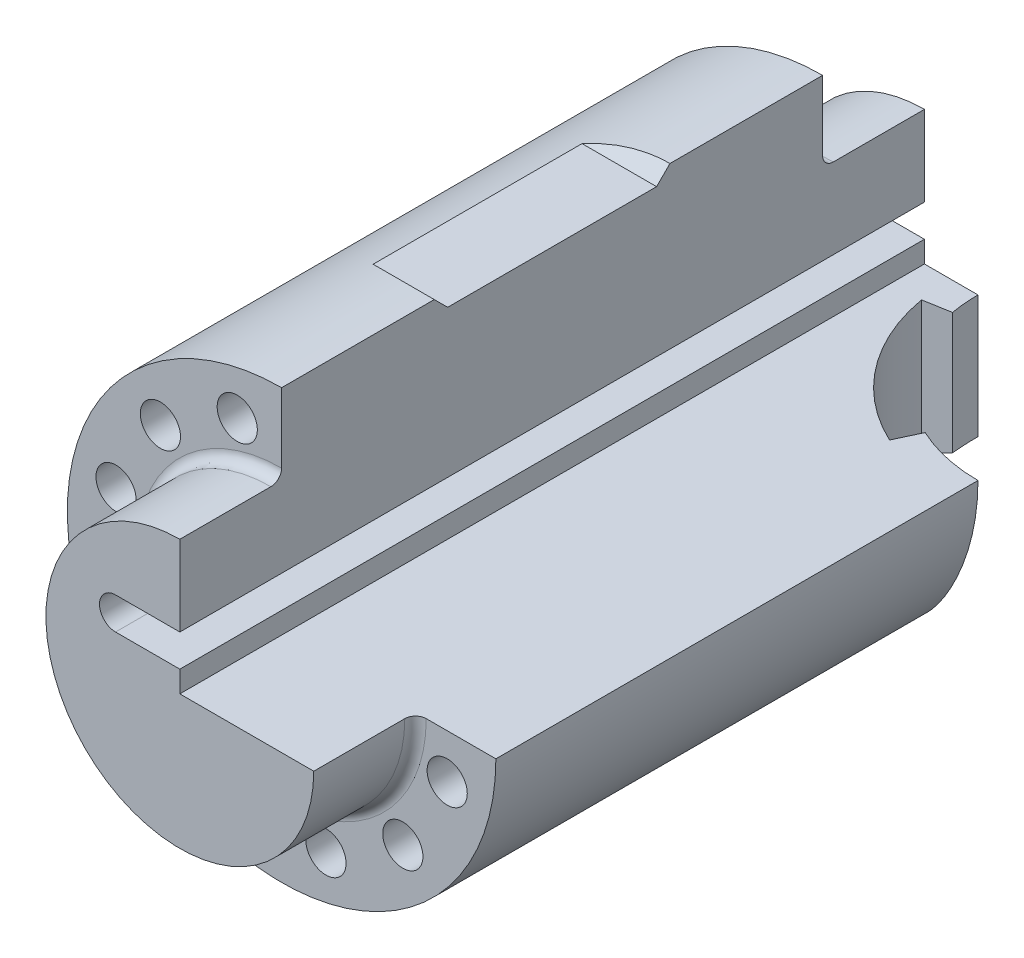
SolidWorks part; units mm, degrees
material "AISI 1020"
ref_plane "Front Plane" through (0, 0, 0) normal (0, 0, 1) x (1, 0, 0)
ref_plane "Top Plane" through (0, 0, 0) normal (0, 1, 0) x (1, 0, 0)
ref_plane "Right Plane" through (0, 0, 0) normal (1, 0, 0) x (0, 0, -1)
sketch "Sketch1" plane through (0, 0, 0) normal (0, 0, 1) x (1, 0, 0)
  circle A0 centre (0, 0) radius 40
  dimension "D1" = 80
extrude "Boss-Extrude1" add sketch "Sketch1" against normal blind 139
sketch "Sketch2" plane through (0, 0, 0) normal (0, 0, 1) x (1, 0, 0)
  circle A1 centre (0, 0) radius 25
  circle M2 centre (0, 0) radius 40
  dimension "D1" = 50
extrude "Cut-Extrude1" cut sketch "Sketch2" against normal blind 19 contours A1 M2
sketch "Sketch3" plane through (0, 0, -139) normal (0, 0, -1) x (-1, 0, 0)
  circle A0 centre (0, 0) radius 25
  circle M2 centre (0, 0) radius 40
  dimension "D1" = 50
extrude "Cut-Extrude2" cut sketch "Sketch3" against normal blind 19 contours A0 M2
fillet "Fillet1" radius 2 2 edges at (-25, 0, -120) (25, 0, -19)
sketch "Sketch5" plane through (0, 0, 0) normal (0, 0, 1) x (1, 0, 0)
  line L0 (0, 40) -> (0, 0)
  line L1 (0, 0) -> (40, 0)
  line L2 (40, 0) -> (0, 40)
  circle A0 centre (0, 0) radius 40 construction
extrude "Cut-Extrude7" cut sketch "Sketch5" against normal through all
sketch "Sketch6" plane through (0, 0, 0) normal (0, 0, 1) x (1, 0, 0)
  line L0 (12, 7) -> (-12, 7) construction
  line L1 (0, 25) -> (0, 0) construction
  line L2 (12, 4) -> (-12, 4)
  line L3 (12, 10) -> (-12, 10)
  arc A0 (12, 4) -> (12, 10) centre (12, 7) ccw
  arc A1 (-12, 10) -> (-12, 4) centre (-12, 7) ccw
  point P4 (0, 7)
  dimension "D1" = 3
  dimension "D2" = 7
  dimension "D3" = 12
extrude "Cut-Extrude8" cut sketch "Sketch6" against normal through all
sketch "Sketch7" plane through (0, 0, 0) normal (1, 0, 0) x (0, 0, -1)
  line L0 (19, 40) -> (47.5, 40)
  line L1 (120, 40) -> (19, 40) construction
  line L2 (47.5, 40) -> (50, 37.5)
  line L3 (50, 37.5) -> (89, 37.5)
  line L4 (89, 37.5) -> (91.5, 40)
  line L5 (91.5, 40) -> (120, 40)
  line L6 (120, 40) -> (120, 10)
  line L7 (139, 10) -> (0, 10) construction
  line L8 (120, 10) -> (19, 10)
  line L9 (19, 10) -> (19, 40)
  line M15 (120, 40) -> (19, 40)
  dimension "D1" = 28.5
  dimension "D2" = 28.5
  dimension "D3" = 2.5
  dimension "D4" = 45
extrude "Cut-Extrude9" cut sketch "Sketch7" against normal through all contours L3 L4 L2 M15
sketch "Sketch8" plane through (0, 0, 0) normal (0, 0, 1) x (1, 0, 0)
  line L6 (0, 0) -> (0, 4) construction
  line L7 (-12, 4) -> (0, 4) construction
  line L8 (0, 0) -> (-15.4809, 57.7756) construction
  line L9 (0, 40) -> (0, 27) construction
  circle A0 centre (0, 0) radius 32 construction
  circle A1 centre (-8.2822, 30.9096) radius 3.75
  dimension "D1" = 64
  dimension "D2" = 7.5
  dimension "D3" = 15
extrude "Cut-Extrude10" cut sketch "Sketch8" against normal through all
pattern_circular "CirPattern1" count 12 every 30 about axis through (0, 0, -19) along (0, 0, 1) of "Cut-Extrude10"
sketch "Sketch9" plane through (0, 0, 0) normal (0, 1, 0) x (1, 0, 0)
  line L0 (25, 139) -> (61.9057, 139) construction
  line L1 (0, 139) -> (25, 139) construction
  line L2 (40, 109) -> (40, 149.9774) construction
  line L3 (40, 19) -> (40, 120) construction
  line L4 (25, 139) -> (25, 136.3551)
  line L5 (25, 122) -> (25, 139) construction
  line L7 (10, 139) -> (40, 139)
  line L10 (40, 139) -> (40, 109)
  line L11 (40, 139) -> (25.2084, 107.2792)
  line L13 (40, 139) -> (5.5317, 132.9223)
  arc A0 (10, 139) -> (40, 109) centre (40, 139) ccw
  arc A1 (5.5317, 132.9223) -> (25.2084, 107.2792) centre (40, 139) ccw
  point P9 (0, 0)
  point P10 (40, 106.6617)
  point P11 (40, 108.6994)
  dimension "D1" = 60
  dimension "D2" = 70
  dimension "D3" = 10
  dimension "D4" = 25
extrude "Cut-Extrude14" cut sketch "Sketch9" against normal through all contours L7 A0 L10 | L13 A1 L11
equation "\"A\"= 139.0"
equation "\"B\"= 19"
equation "\"C\"= 28.50"
